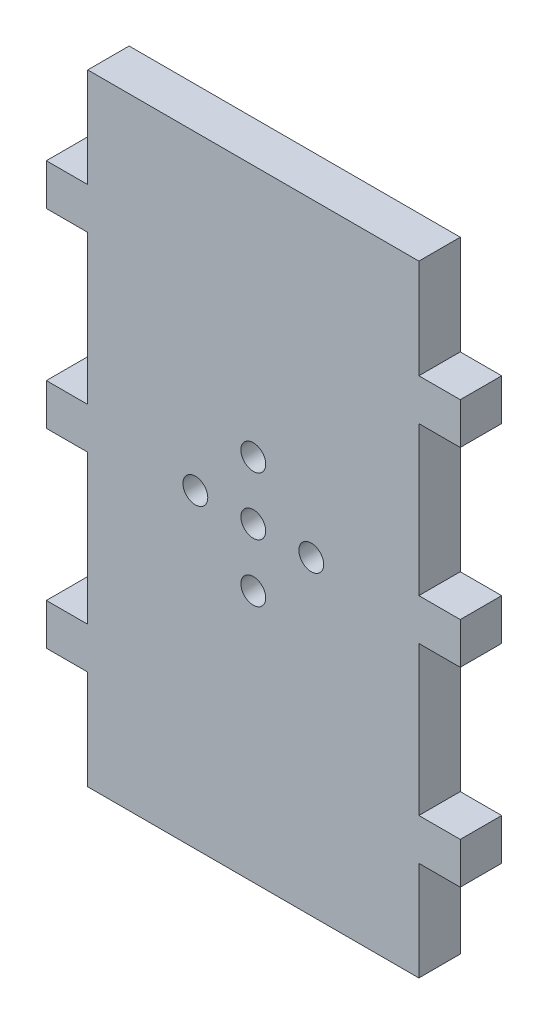
SolidWorks part; units mm, degrees
ref_plane "前视基准面" through (0, 0, 0) normal (0, 0, 1) x (1, 0, 0)
ref_plane "上视基准面" through (0, 0, 0) normal (0, 1, 0) x (1, 0, 0)
ref_plane "右视基准面" through (0, 0, 0) normal (1, 0, 0) x (0, 0, -1)
other "Configuration Table"
sketch "草图3" plane through (0, 0, 0) normal (0, 0, 1) x (1, 0, 0)
  line L0 (0, 9.9703) -> (0, -2.0297)
  line L1 (0, 9.9703) -> (40, 9.9703)
  line L3 (0, -65.0297) -> (40, -65.0297)
  line L4 (40, 9.9703) -> (40, -2.0297)
  line L5 (-5, -2.0297) -> (-5, -7.0297)
  line L6 (20, 9.9703) -> (20, -65.0297) construction
  line L7 (40, -2.0297) -> (45, -2.0297)
  line L8 (45, -2.0297) -> (45, -7.0297)
  line L9 (45, -7.0297) -> (40, -7.0297)
  line L10 (40, -7.0297) -> (40, -25.0297)
  line L11 (40, -25.0297) -> (45, -25.0297)
  line L12 (45, -25.0297) -> (45, -30.0297)
  line L13 (45, -30.0297) -> (40, -30.0297)
  line L14 (40, -65.0297) -> (40, -53.0297)
  line L15 (40, -53.0297) -> (45, -53.0297)
  line L16 (45, -53.0297) -> (45, -48.0297)
  line L17 (45, -48.0297) -> (40, -48.0297)
  line L18 (-5, -48.0297) -> (0, -48.0297)
  line L19 (-5, -53.0297) -> (-5, -48.0297)
  line L20 (0, -53.0297) -> (-5, -53.0297)
  line L21 (-5, -30.0297) -> (0, -30.0297)
  line L22 (-5, -25.0297) -> (-5, -30.0297)
  line L23 (0, -25.0297) -> (-5, -25.0297)
  line L24 (-5, -7.0297) -> (0, -7.0297)
  line L26 (0, -2.0297) -> (-5, -2.0297)
  line L27 (0, -7.0297) -> (0, -25.0297)
  line L28 (0, -30.0297) -> (0, -48.0297)
  line L29 (0, -53.0297) -> (0, -65.0297)
  line L31 (40, -30.0297) -> (40, -48.0297)
  circle A0 centre (20, -27.53) radius 1.5
  circle A2 centre (27, -27.53) radius 1.5
  circle A3 centre (20, -20.53) radius 1.5
  circle A4 centre (13, -27.53) radius 1.5
  circle A5 centre (20, -34.53) radius 1.5
  dimension "D6" = 3
  dimension "D12" = 3
  dimension "D13" = 3
  dimension "D14" = 3
  dimension "D1" = 75
  dimension "D2" = 40
  dimension "D3" = 12
  dimension "D4" = 5
  dimension "D5" = 5
  dimension "D7" = 5
  dimension "D8" = 5
  dimension "D9" = 12
  dimension "D10" = 5
  dimension "D11" = 5
  dimension "D15" = 23
  dimension "D16" = 37.5003
  dimension "D17" = 37.5003
  dimension "D18" = 30.5003
  dimension "D19" = 37.5003
  dimension "D20" = 44.5003
extrude "凸台-拉伸2" add sketch "草图3" along normal blind 5
